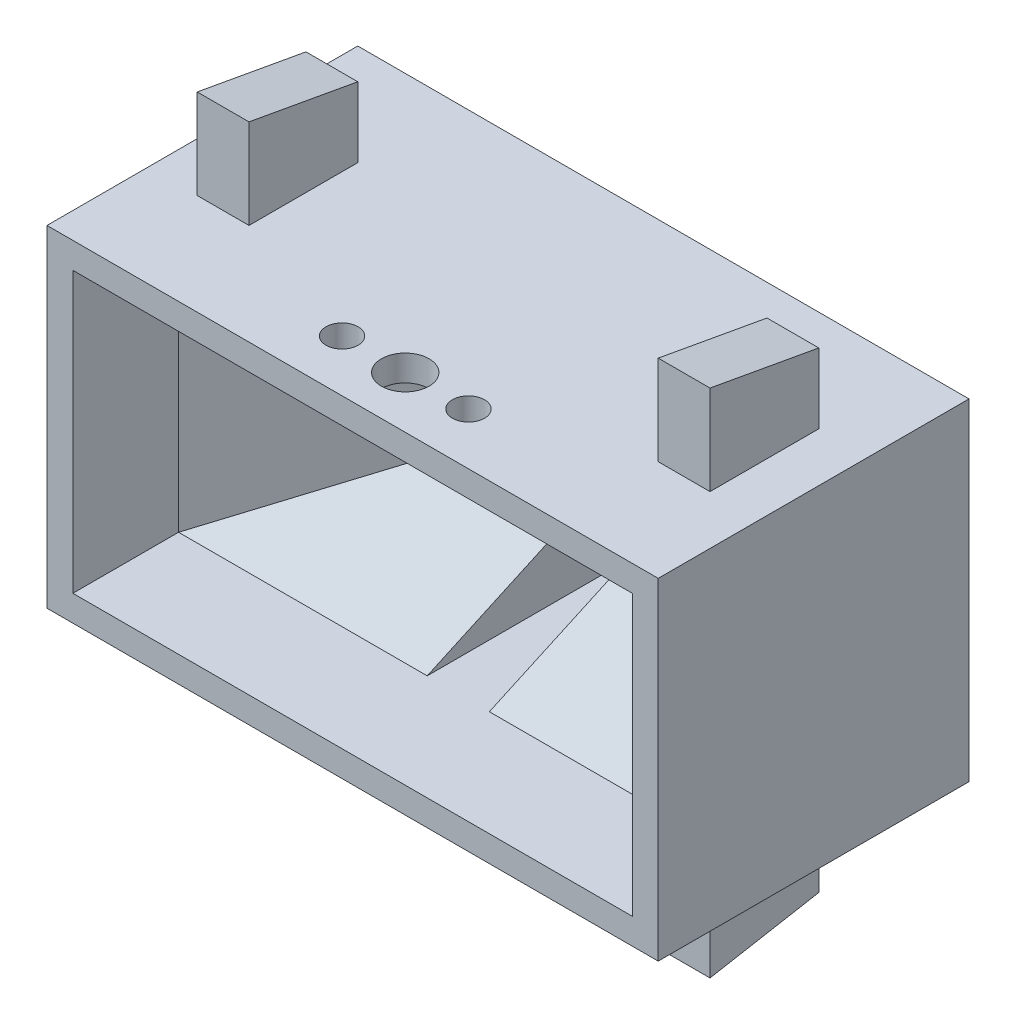
SolidWorks part; units mm, degrees
ref_plane "Alzado" through (0, 0, 0) normal (0, 0, 1) x (1, 0, 0)
ref_plane "Planta" through (0, 0, 0) normal (0, 1, 0) x (1, 0, 0)
ref_plane "Vista lateral" through (0, 0, 0) normal (1, 0, 0) x (0, 0, -1)
sketch "Croquis1" plane through (0, 0, 0) normal (0, 0, 1) x (1, 0, 0)
  line L1 (-27, -13.5) -> (27, -13.5)
  line L2 (-27, -13.5) -> (-27, 13.5)
  line L3 (-27, 13.5) -> (27, 13.5)
  line L4 (27, -13.5) -> (27, 13.5)
  line L5 (-27, -13.5) -> (27, 13.5) construction
  line L6 (-27, 13.5) -> (27, -13.5) construction
  point P0 (0, 0)
  dimension "D1" = 27
  dimension "D2" = 54
extrude "Saliente-Extruir1" add sketch "Croquis1" along normal blind 14.8
sketch "Croquis5" plane through (0, 0, 14.8) normal (0, 0, 1) x (1, 0, 0)
  line L0 (-27, 13.5) -> (-27, -13.5)
  line L1 (-27, -13.5) -> (27, -13.5)
  line L2 (27, -13.5) -> (27, 13.5)
  line L3 (27, 13.5) -> (-27, 13.5)
  point P4 (0, 0)
  dimension "D1" = 27
  dimension "D2" = 54
sketch "Croquis6" plane through (0, 0, 0) normal (0, 0, -1) x (-1, 0, 0)
  line L0 (0, 13.5) -> (0, 6.75) construction
  line L1 (-13.5, -6.75) -> (13.5, -6.75)
  line L2 (-13.5, -6.75) -> (-13.5, 6.75)
  line L3 (-13.5, 6.75) -> (13.5, 6.75)
  line L4 (13.5, -6.75) -> (13.5, 6.75)
  line L5 (-27, 13.5) -> (27, 13.5) construction
  line L6 (0, -6.75) -> (0, -13.5) construction
  line L7 (27, -13.5) -> (-27, -13.5) construction
  point P0 (0, 0)
  dimension "D1" = 13.5
  dimension "D2" = 27
loft "Cortar-Recubrir3" cut profiles "Croquis5", "Croquis6"
sketch "Croquis8" plane through (0, 0, 0) normal (0, 0, -1) x (-1, 0, 0)
  line L1 (3, -13.5) -> (-3, -13.5)
  line L2 (3, -13.5) -> (3, 13.5)
  line L3 (3, 13.5) -> (-3, 13.5)
  line L4 (-3, -13.5) -> (-3, 13.5)
  line L5 (3, -13.5) -> (-3, 13.5) construction
  line L6 (3, 13.5) -> (-3, -13.5) construction
  point P0 (0, 0)
  dimension "D1" = 6
  dimension "D2" = 27
extrude "Cortar-Extruir2" cut sketch "Croquis8" against normal blind 14.8
sketch "Croquis10" plane through (0, 0, 0) normal (1, 0, 0) x (0, 0, -1)
  line L0 (-14.8, 13.5) -> (-25, 13.5)
  line L1 (-25, 13.5) -> (-25, 15.75)
  line L2 (-25, -13.5) -> (-25, -15.75)
  line L4 (-25, 15.75) -> (-25, 16)
  line L5 (-14.8, -13.5) -> (0, -13.5)
  line L6 (5, 15) -> (5, 16)
  line L7 (5, 16) -> (-24.6808, 16)
  line L8 (-25, 16) -> (-24.6808, 16)
  line L9 (5, 15) -> (5, -16)
  line L10 (-14.8, -13.5) -> (-25, -13.5)
  line L11 (-25, -15.75) -> (-25, -16)
  line L12 (0, -13.5) -> (0, 13.5) construction
  line L13 (-25, 13.5) -> (-25, -13.5) construction
  line L14 (-25, -16) -> (-24.6808, -16)
  line L15 (5, -16) -> (-24.6808, -16)
  line L21 (0, -13.5) -> (0, 13.5)
  line L22 (0, 13.5) -> (-14.8, 13.5)
  dimension "D3" = 10.2
  dimension "D4" = 2.5
  dimension "D5" = 5
  dimension "D8" = 2.5
extrude "Saliente-Extruir2" add sketch "Croquis10" along normal blind 35 and the other way blind 35
sketch "Croquis12" plane through (0, 0, 0) normal (0, 0, 1) x (1, 0, 0)
  line L0 (27, 13.5) -> (35, 13.5) construction
  line L1 (-27, -13.5) -> (27, -13.5)
  line L2 (-27, -13.5) -> (-27, 13.5)
  line L3 (-27, 13.5) -> (27, 13.5)
  line L4 (27, -13.5) -> (27, 13.5)
  line L5 (-27, -13.5) -> (27, 13.5) construction
  line L6 (-27, 13.5) -> (27, -13.5) construction
  line L7 (-29.5, -13.5) -> (29.5, -13.5)
  line L8 (-29.5, -13.5) -> (-29.5, 13.5)
  line L9 (-29.5, 13.5) -> (29.5, 13.5)
  line L10 (29.5, -13.5) -> (29.5, 13.5)
  line L11 (-29.5, -13.5) -> (29.5, 13.5) construction
  line L12 (-29.5, 13.5) -> (29.5, -13.5) construction
  point P0 (0, 0)
  point P5 (0, 0)
  dimension "D1" = 2.5
  dimension "D2" = 54
  dimension "D3" = 27
extrude "Saliente-Extruir3" add sketch "Croquis12" along normal blind 25 contours L9 L8 L7 L2 | L7 L10 L9 L4
sketch "Croquis19" plane through (0, 16, 0) normal (0, 1, 0) x (1, 0, 0)
  line L1 (-35, 5) -> (35, 5)
  line L2 (-35, 5) -> (-35, -25)
  line L3 (-35, -25) -> (35, -25)
  line L4 (35, 5) -> (35, -25)
  line L5 (-35, 5) -> (35, -25) construction
  line L6 (-35, -25) -> (35, 5) construction
  line L7 (-29.5, -25) -> (29.5, -25)
  line L8 (-29.5, -25) -> (-29.5, 5)
  line L9 (-29.5, 5) -> (29.5, 5)
  line L10 (29.5, -25) -> (29.5, 5)
  line L11 (-29.5, -25) -> (29.5, 5) construction
  line L12 (-29.5, 5) -> (29.5, -25) construction
  point P0 (0, -10)
  point P5 (0, -10)
  line M1 (-35, -25) -> (35, -25)
  line M2 (35, -25) -> (35, 5)
  line M3 (35, 5) -> (-35, 5)
  line M4 (-35, 5) -> (-35, -25)
  dimension "D1" = 59
  dimension "D2" = 30
extrude "Cortar-Extruir15" cut sketch "Croquis19" against normal through all contours L8 L1 M1 M4 | L10 M1 M2 M3
sketch "Croquis18" plane through (0, 16, 0) normal (0, 1, 0) x (1, 0, 0)
  line L0 (-29.5, 5) -> (29.5, 5) construction
  line L1 (-29.5, 5) -> (29.5, 5) construction
  circle A0 centre (0.0814, -19.9999) radius 2.3
  circle A1 centre (6.1814, -20) radius 1.55
  circle A2 centre (-6.0186, -20) radius 1.55
  point P2 (0, 5)
  dimension "D1" = 4.6
  dimension "D3" = 3.1
  dimension "D4" = 3.1
  dimension "D2" = 25
  dimension "D5" = 6.1
  dimension "D6" = 6.1
  dimension "D7" = 25
  dimension "D8" = 25
extrude "Cortar-Extruir12" cut sketch "Croquis18" against normal blind 2.5
sketch "Croquis20" plane through (0, 0, 0) normal (0, 0, 1) x (1, 0, 0)
  line L0 (-3, 13.5) -> (3, 13.5)
  line L1 (3, 13.5) -> (3, 9.625)
  line L2 (3, 9.625) -> (-3, 9.625)
  line L3 (-3, 9.625) -> (-3, 13.5)
  line L4 (-3, -13.5) -> (3, -13.5)
  line L5 (3, -13.5) -> (3, -9.625)
  line L6 (3, -9.625) -> (-3, -9.625)
  line L7 (-3, -9.625) -> (-3, -13.5)
  dimension "D1" = 3.875
  dimension "D2" = 3.875
extrude "Cortar-Extruir16" cut sketch "Croquis20" against normal through all
sketch "Croquis22" plane through (29.5, 0, 0) normal (1, 0, 0) x (0, 0, -1)
  line L0 (5, 16) -> (5, 21)
  line L1 (-115, 37.6154) -> (-113.7059, 42.4451)
  line L2 (-25, 16) -> (-25, 13.5)
  line L3 (-25, 13.5) -> (-115, 37.6154)
  line L4 (-113.7059, 42.4451) -> (5, 21)
  line L5 (5, 16) -> (-25, 16)
  line L6 (-10, 16) -> (-10, 23.7099) construction
  line L7 (-4.75, 16) -> (-4.75, 22.7614)
  line L8 (-15.25, 16) -> (-15.25, 24.6583)
  line L9 (5, 0) -> (-25, 0) construction
  line L10 (5, -16) -> (5, 16) construction
  line L11 (-25, -16) -> (-25, 16) construction
  line L12 (-115, -37.6154) -> (-113.7059, -42.4451)
  line L13 (-25, -13.5) -> (-115, -37.6154)
  line L14 (-25, -16) -> (-25, -13.5)
  line L15 (5, -16) -> (5, -21)
  line L16 (-15.25, -16) -> (-15.25, -24.6583)
  line L17 (-113.7059, -42.4451) -> (5, -21)
  line L18 (-4.75, -16) -> (-4.75, -22.7614)
  line L19 (5, -16) -> (-25, -16)
  dimension "D1" = 75
  dimension "D2" = 5
  dimension "D3" = 90
  dimension "D4" = 5
  dimension "D5" = 5.25
  dimension "D6" = 5.25
extrude "Saliente-Extruir4" add sketch "Croquis22" against normal blind 59 separate body
sketch "Croquis23" plane through (0, 0, 15.25) normal (0, 0, 1) x (1, 0, 0)
  line L0 (-29.5, 20.3292) -> (29.5, 20.3292)
  line L1 (-29.5, 24.6583) -> (29.5, 24.6583)
  line L2 (-29.5, 24.6583) -> (-29.5, 16)
  line L3 (-29.5, 16) -> (29.5, 16)
  line L4 (29.5, 24.6583) -> (29.5, 16)
  line L5 (-29.5, 0) -> (29.5, 0) construction
  line L6 (-24.75, 16) -> (-19.75, 16)
  line L7 (-24.75, 16) -> (-24.75, 24.6583)
  line L8 (-24.75, 24.6583) -> (-19.75, 24.6583)
  line L9 (-19.75, 16) -> (-19.75, 24.6583)
  line L10 (-24.75, 16) -> (-19.75, 24.6583) construction
  line L11 (-24.75, 24.6583) -> (-19.75, 16) construction
  line L12 (19.75, 16) -> (24.75, 16)
  line L13 (19.75, 16) -> (19.75, 24.6583)
  line L14 (19.75, 24.6583) -> (24.75, 24.6583)
  line L15 (24.75, 16) -> (24.75, 24.6583)
  line L16 (19.75, 16) -> (24.75, 24.6583) construction
  line L17 (19.75, 24.6583) -> (24.75, 16) construction
  line L18 (-29.5, -16) -> (-29.5, 16) construction
  line L19 (29.5, -16) -> (29.5, 16) construction
  line L20 (29.5, -24.6583) -> (29.5, -16)
  line L21 (24.75, -16) -> (24.75, -24.6583)
  line L22 (19.75, -16) -> (19.75, -24.6583)
  line L23 (-19.75, -16) -> (-19.75, -24.6583)
  line L24 (-24.75, -16) -> (-24.75, -24.6583)
  line L25 (-29.5, -24.6583) -> (-29.5, -16)
  line L26 (-29.5, -16) -> (29.5, -16)
  line L27 (-29.5, -24.6583) -> (29.5, -24.6583)
  point P8 (-22.25, 20.3292)
  point P13 (22.25, 20.3292)
  line M1 (29.5, 16) -> (29.5, 24.6583)
  line M2 (29.5, 24.6583) -> (-29.5, 24.6583)
  line M3 (-29.5, 24.6583) -> (-29.5, 16)
  line M4 (-29.5, 16) -> (29.5, 16)
  dimension "D1" = 7.25
  dimension "D2" = 7.25
  dimension "D3" = 5
  dimension "D4" = 5
extrude "Cortar-Extruir17" cut sketch "Croquis23" against normal through all contours L0 L7 L1 M3 | L7 L0 M4 M3 | L13 L0 L9 M4 | L0 L13 L1 L9 | L15 L0 M1 M2 | L15 L0 M4 M1 | L23 L27 L22 L26 | L21 L27 L20 L26 | L25 L27 L24 L26
equation "\"CAJA_H\"= 30"
equation "\"D1@Croquis1\"=\"A_CAJA\""
equation "\"CAJA_W\"= 46"
equation "\"D2@Croquis1\"=\"W_CAJA\""
equation "\"D1@Croquis6\"=\"A_CONC\""
equation "\"D2@Croquis6\"=\"W_CONC\""
equation "\"D1@Croquis7\" = \"CAJA_H\""
equation "\"J_D\"= 6"
equation "\"D1@Croquis8\"=\"E_ALETA\"+\"TOLERANCIA\""
equation "\"D2@Croquis8\"=\"A_CAJA\""
equation "\"G\"= 2.5"
equation "\"D4@Croquis10\"=\"E_CAJA\""
equation "\"H\"= 39"
equation "\"D1@Croquis10\" = \"H\""
equation "\"L\"= 70"
equation "\"D2@Croquis10\" = \"L\""
equation "\"L2\"= 27"
equation "\"D3@Croquis10\"=\"L_CAJA\"-\"L_CONC\""
equation "\"D7@Croquis10\" = \"H\""
equation "\"D8@Croquis10\"=\"E_CAJA\""
equation "\"D1@Croquis12\"=\"E_CAJA\""
equation "\"D1@Croquis13\" = \"CAJA_H\""
equation "\"R\"= 4.15"
equation "\"D1@Croquis18\"=( 2 * \"R_SONDA\" ) +\"TOLERANCIA\""
equation "\"BASE\"= 14"
equation "\"A_ALETA\"= ( ( ( tan ( \"ANG_ALETA\" ) ) * \"L_ALETA\" ) + \"A_BASE\" )"
equation "\"A_BASE\"= ( \"L_DIE\" - \"E_CAJA\" )"
equation "\"L_ALETA\"=90.000000"
equation "\"TAU_ALETA\"= ( \"L_ALETA\" / ( log ( ( \"A_ALETA\" ) + 1 ) ) )"
equation "\"E_ALETA\"=5.5"
equation "\"R_SONDA\"= 2.05"
equation "\"D_SONDA\"=20.000000"
equation "\"L_CAJA\"=25.000000"
equation "\"E_CAJA\"= 2.5"
equation "\"A_CAJA\"= ( 2 * \"A_BASE\" ) + \"GAP_ALETAS\""
equation "\"W_CAJA\"= \"A_CAJA\" * \"CONST_CAJA\""
equation "\"W_CONC\"= ( \"W_CAJA\" / \"CONST_CONC\" ) "
equation "\"A_CONC\"= ( \"A_CAJA\" / \"CONST_CONC\" )"
equation "\"L_CONC\"= \"D_SONDA\" - \"OFFSET_CONC\""
equation "\"W_ALETA\"=70.000000"
equation "\"GAP_ALETAS\"=2"
equation "\"D1@Saliente-Extruir1\"=\"L_CONC\""
equation "\"D1@Cortar-Extruir2\"=\"L_CONC\""
equation "\"D1@Saliente-Extruir2\"=\"W_ALETA\"/2"
equation "\"D2@Saliente-Extruir2\"=\"W_ALETA\"/2"
equation "\"D5@Croquis10\" = \"E_CAJA\" * 2"
equation "\"D1@Saliente-Extruir3\"=\"L_CAJA\""
equation "\"D1@Cortar-Extruir8\" = \"E_CAJA\""
equation "\"D2@Croquis18\" = \"D_SONDA\" + \"E_CAJA\" * 2"
equation "\"D1@Cortar-Extruir12\"=\"E_CAJA\""
equation "\"L_DIE_SONDA\"= ( \"GAP_ALETAS\" / 4 )"
equation "\"CONST_CONC\"=2.000000"
equation "\"K\"= 1.5"
equation "\"L_DIE\"= 15"
equation "\"L_CI\"= 18"
equation "\"CONST_CAJA\"=2.000000"
equation "\"ANG_ALETA\"=15.000000"
equation "\"R_C_SONDA\"= 0.63"
equation "\"TOLERANCIA\"= 0.5"
equation "\"OFFSET_CONC\"= ( 2 * \"R_TORNILLO\" )"
equation "\"R_TORNILLO\"=2.600000"
equation "\"D4@Croquis18\"=\"R_TORNILLO\"+\"TOLERANCIA\""
equation "\"D3@Croquis18\"=\"R_TORNILLO\"+\"TOLERANCIA\""
equation "\"D7@Croquis18\"=\"D_SONDA\"+ \"E_CAJA\"*2"
equation "\"D8@Croquis18\"=\"D_SONDA\"+ \"E_CAJA\"*2"
equation "\"D1@Croquis19\"=\"W_CAJA\"+\"E_CAJA\"*2"
equation "\"D2@Croquis19\"=\"L_CAJA\"+\"E_CAJA\"*2"
equation "\"D1@Croquis20\"=( \"A_CAJA\" - \"A_CONC\" )/4 +\"TOLERANCIA\""
equation "\"D2@Croquis20\"=( \"A_CAJA\" - \"A_CONC\" )/4 +\"TOLERANCIA\""
equation "\"D2@Croquis22\" = \"E_CAJA\" * 2"
equation "\"D1@Croquis22\"=90-\"ANG_ALETA\""
equation "\"D3@Croquis22\"=\"L_ALETA\""
equation "\"D4@Croquis22\"=\"E_CAJA\"*2"
equation "\"D5@Croquis22\"=(\"TOLERANCIA\")/2 + 5"
equation "\"D6@Croquis22\"=(\"TOLERANCIA\")/2 + 5"
equation "\"D1@Saliente-Extruir4\"=\"W_CAJA\"+\"E_CAJA\"*2"
equation "\"D1@Croquis23\"=(\"W_CAJA\"-\"L_CAJA\")/4"
equation "\"D2@Croquis23\"=(\"W_CAJA\"-\"L_CAJA\")/4"
equation "\"ALARGUE\"=15"
